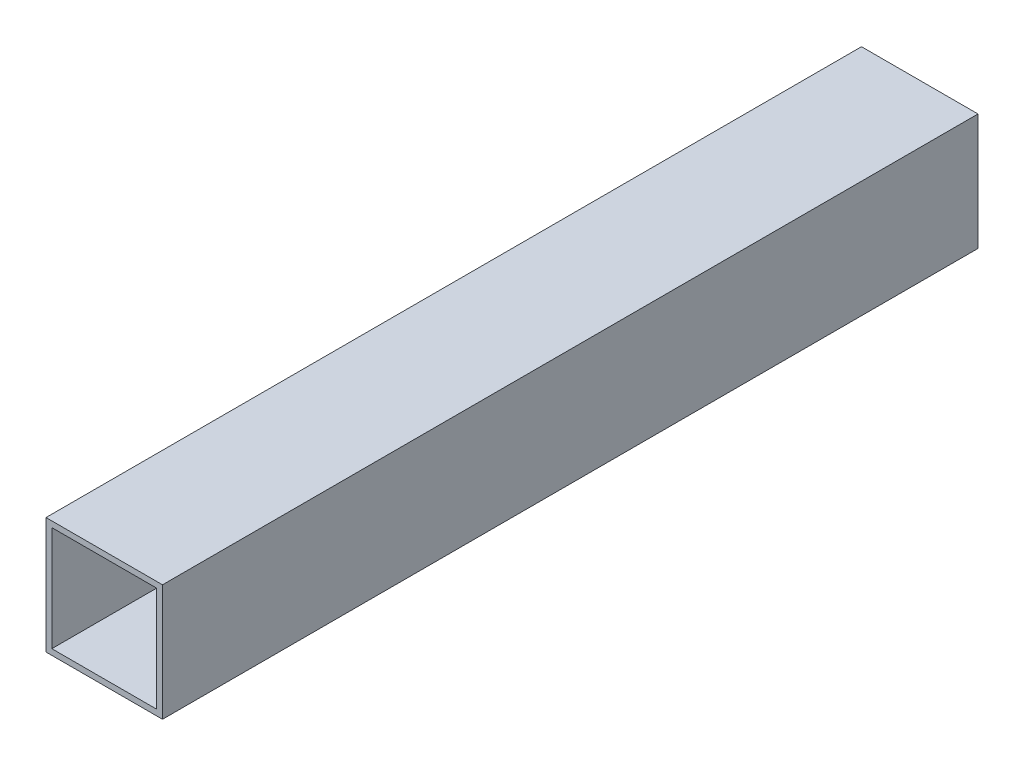
SolidWorks part; units mm, degrees
material "Glass"
ref_plane "Front Plane" through (0, 0, 0) normal (0, 0, 1) x (1, 0, 0)
ref_plane "Top Plane" through (0, 0, 0) normal (0, 1, 0) x (1, 0, 0)
ref_plane "Right Plane" through (0, 0, 0) normal (1, 0, 0) x (0, 0, -1)
sketch "Sketch1" plane through (0, 0, 0) normal (0, 0, 1) x (1, 0, 0)
  line L1 (1.6329, 0) -> (52.4329, 0)
  line L2 (1.6329, 0) -> (1.6329, 50.8)
  line L3 (1.6329, 50.8) -> (52.4329, 50.8)
  line L4 (52.4329, 0) -> (52.4329, 50.8)
  line L5 (4.1729, 2.54) -> (49.8929, 2.54)
  line L6 (4.1729, 2.54) -> (4.1729, 48.26)
  line L7 (4.1729, 48.26) -> (49.8929, 48.26)
  line L8 (49.8929, 2.54) -> (49.8929, 48.26)
  dimension "D1" = 50.8
  dimension "D2" = 50.8
  dimension "D3" = 45.72
  dimension "D4" = 45.72
  dimension "D5" = 2.54
  dimension "D6" = 2.54
extrude "Boss-Extrude1" add sketch "Sketch1" along normal blind 355.6
